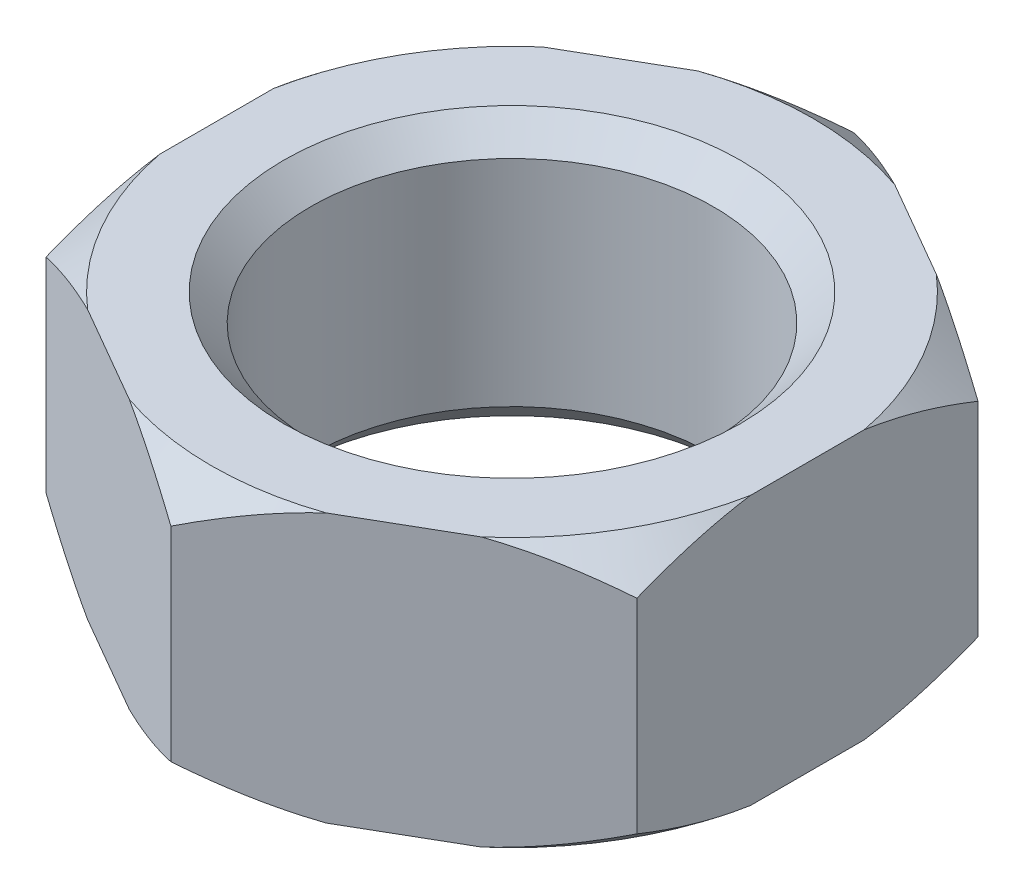
SolidWorks part; units mm, degrees
ref_plane "Front Plane" through (0, 0, 0) normal (0, 0, 1) x (1, 0, 0)
ref_plane "Top Plane" through (0, 0, 0) normal (0, 1, 0) x (1, 0, 0)
ref_plane "Right Plane" through (0, 0, 0) normal (1, 0, 0) x (0, 0, -1)
sketch "Sketch1" plane through (0, 0, 0) normal (0, 1, 0) x (1, 0, 0)
  line L1 (0, 12.7017) -> (-11, 6.3509)
  line L2 (-11, 6.3509) -> (-11, -6.3509)
  line L3 (-11, -6.3509) -> (0, -12.7017)
  line L4 (0, -12.7017) -> (11, -6.3509)
  line L5 (11, -6.3509) -> (11, 6.3509)
  line L6 (11, 6.3509) -> (0, 12.7017)
  circle A0 centre (0, 0) radius 11 construction
  point P10 (11, 0)
  dimension "D1" = 22
extrude "Boss-Extrude1" add sketch "Sketch1" along normal blind 10
sketch "Sketch2" plane through (0, 10, 0) normal (0, 1, 0) x (1, 0, 0)
  circle A0 centre (0, 0) radius 7.5
  dimension "D1" = 15
extrude "Cut-Extrude1" cut sketch "Sketch2" against normal through all
cosmetic thread "Cosmetic Thread1" parameters "D2"=24
chamfer "Chamfer1" distance 1 angle 45 2 edges at (0, 10, 7.5) (0, 0, 7.5)
sketch "Sketch3" plane through (0, 0, 0) normal (1, 0, 0) x (0, 0, -1)
  line L0 (0, 13.3815) -> (0, -4.0939) construction
  line L1 (-12.7017, 10) -> (-12.7017, 8.8)
  line L2 (-12.7017, 10) -> (-12.7017, 0) construction
  line L3 (-12.7017, 8.8) -> (-11.2017, 10)
  line L4 (-12.7017, 10) -> (-6.3509, 10) construction
  line L5 (-11.2017, 10) -> (-12.7017, 10)
  line L6 (-12.7017, 0) -> (-12.7017, 1.2)
  line L7 (-12.7017, 1.2) -> (-11.2017, 0)
  line L8 (-12.7017, 0) -> (-6.3509, 0) construction
  line L9 (-11.2017, 0) -> (-12.7017, 0)
  dimension "D1" = 1.2
  dimension "D2" = 1.5
  dimension "D3" = 1.5
  dimension "D4" = 1.2
revolve "Cut-Revolve1" cut sketch "Sketch3" angle 360 about L0
